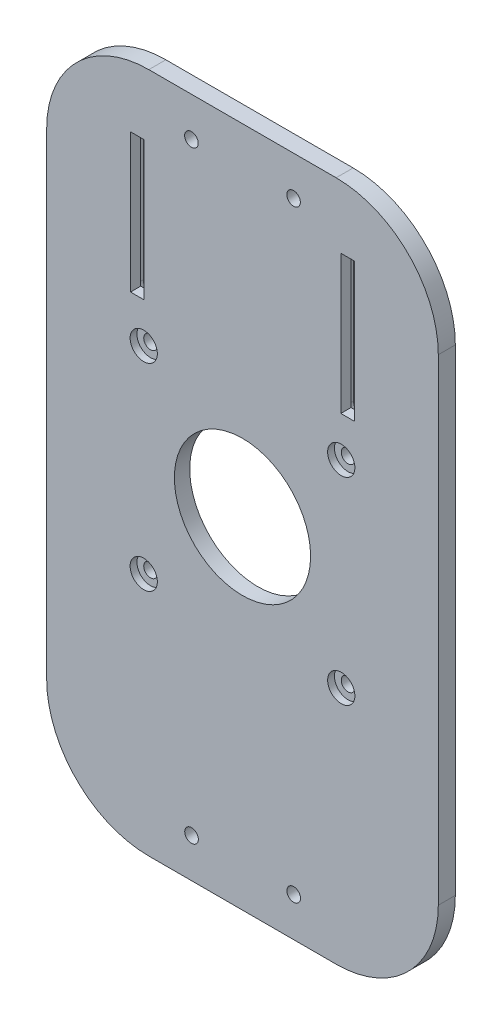
SolidWorks part; units mm, degrees
ref_plane "Front Plane" through (0, 0, 0) normal (1, 0, 0) x (0, 1, 0)
ref_plane "Top Plane" through (0, 0, 0) normal (0, 0, 1) x (0, 1, 0)
ref_plane "Right Plane" through (0, 0, 0) normal (0, 1, 0) x (-1, 0, 0)
sketch "Sketch1" plane through (0, 0, 0) normal (0, 0, 1) x (0, 1, 0)
  line L1 (-100, -57.5) -> (100, -57.5)
  line L2 (-100, -57.5) -> (-100, 57.5)
  line L3 (-100, 57.5) -> (100, 57.5)
  line L4 (100, -57.5) -> (100, 57.5)
  line L5 (-100, -57.5) -> (100, 57.5) construction
  line L6 (-100, 57.5) -> (100, -57.5) construction
  circle A0 centre (0, 0) radius 20
  point P0 (0, 0)
  dimension "D3" = 40
  dimension "D1" = 115
  dimension "D2" = 200
extrude "Boss-Extrude1" add sketch "Sketch1" along normal blind 5
sketch "Sketch4" plane through (0, 0, 5) normal (0, 0, 1) x (1, 0, 0)
  line L0 (0, 100) -> (0, -100) construction
  line L1 (57.5, 100) -> (-57.5, 100) construction
  line L2 (-57.5, -100) -> (57.5, -100) construction
  line L3 (-57.5, 0) -> (57.5, 0) construction
  line L4 (-57.5, 100) -> (-57.5, -100) construction
  line L5 (57.5, -100) -> (57.5, 100) construction
  circle A0 centre (29, 29) radius 2 construction
  circle A1 centre (-29, 29) radius 2 construction
  circle A2 centre (-29, -29) radius 2 construction
  circle A3 centre (29, -29) radius 2 construction
  circle A4 centre (29, 29) radius 2
  circle A5 centre (-29, 29) radius 2
  circle A6 centre (-29, -29) radius 2
  circle A7 centre (29, -29) radius 2
extrude "Cut-Extrude1" cut sketch "Sketch4" against normal up to next
sketch "Sketch5" plane through (0, 0, 5) normal (0, 0, 1) x (1, 0, 0)
  circle A0 centre (29, 29) radius 2 construction
  circle A1 centre (29, -29) radius 2 construction
  circle A3 centre (-29, 29) radius 2 construction
  circle A6 centre (-29, -29) radius 2 construction
  circle A40 centre (-29, -29) radius 2 construction
  circle A41 centre (-29, 29) radius 2 construction
  circle A42 centre (29, -29) radius 2 construction
  circle A43 centre (29, 29) radius 2 construction
  circle A44 centre (-29, -29) radius 4
  circle A45 centre (-29, 29) radius 4
  circle A46 centre (29, -29) radius 4
  circle A47 centre (29, 29) radius 4
  dimension "D1" = 2
extrude "Cut-Extrude2" cut sketch "Sketch5" against normal blind 2
fillet "Fillet1" radius 30 4 edges at (57.5, 100, 2.5) (-57.5, 100, 2.5) (-57.5, -100, 2.5) (57.5, -100, 2.5)
sketch "Sketch8" plane through (0, 0, 5) normal (0, 0, 1) x (1, 0, 0)
  circle A0 centre (15, 88.5) radius 2
  circle A1 centre (-15, 88.5) radius 2
  circle A2 centre (-14.9609, -88.5) radius 2
  circle A3 centre (15.0391, -88.5) radius 2
extrude "Cut-Extrude4" cut sketch "Sketch8" against normal through all
sketch "Sketch11" plane through (0, 0, 0) normal (0, 0, -1) x (1, 0, 0)
  line L1 (-35.75, -35.75) -> (35.75, -35.75)
  line L2 (-35.75, -35.75) -> (-35.75, 35.75)
  line L3 (-35.75, 35.75) -> (35.75, 35.75)
  line L4 (35.75, -35.75) -> (35.75, 35.75)
  line L5 (-35.75, -35.75) -> (35.75, 35.75) construction
  line L6 (-35.75, 35.75) -> (35.75, -35.75) construction
  point P0 (0, 0)
  dimension "D1" = 71.5
extrude "Cut-Extrude7" cut sketch "Sketch11" against normal blind 0.5
sketch "Sketch9" plane through (0, 0, 5) normal (0, 0, 1) x (1, 0, 0)
  line L0 (0, 0) -> (0, 100) construction
  line L1 (27.5, 100) -> (-27.5, 100) construction
  line L2 (-15.5, 76.5) -> (-15.5, 26.6053) construction
  line L3 (-17.5, 76.5) -> (-17.5, 27) construction
  line L4 (-13.5, 76.5) -> (-13.5, 27) construction
  line L5 (15.5, 76.5) -> (15.5, 26.6053) construction
  line L6 (17.5, 76.5) -> (17.5, 27) construction
  line L7 (13.5, 76.5) -> (13.5, 27) construction
  line L8 (21, 76.5) -> (21, 35.0212) construction
  line L9 (-21, 76.5) -> (-21, 35.0212) construction
  line L10 (28.875, 81.5) -> (28.875, 40.75)
  line L11 (28.875, 40.75) -> (32.875, 40.75)
  line L12 (32.875, 40.75) -> (32.875, 81.5)
  line L13 (32.875, 81.5) -> (28.875, 81.5)
  line L14 (-32.875, 40.75) -> (-32.875, 81.5)
  line L15 (-28.875, 40.75) -> (-32.875, 40.75)
  line L16 (-28.875, 81.5) -> (-28.875, 40.75)
  line L17 (-32.875, 81.5) -> (-28.875, 81.5)
  line L18 (-35.75, 35.75) -> (35.75, 35.75) construction
  arc A0 (-17.5, 76.5) -> (-13.5, 76.5) centre (-15.5, 76.5) cw construction
  arc A1 (-17.5, 27) -> (-13.5, 27) centre (-15.5, 27) ccw construction
  arc A2 (17.5, 76.5) -> (13.5, 76.5) centre (15.5, 76.5) ccw construction
  arc A3 (17.5, 27) -> (13.5, 27) centre (15.5, 27) cw construction
  circle A6 centre (-15, 88.5) radius 2 construction
  circle A11 centre (0, 0) radius 20 construction
  circle A14 centre (15, 88.5) radius 2 construction
  point P41 (-30.875, 81.5)
  point P42 (30.875, 81.5)
  dimension "D3" = 10
  dimension "D4" = 2
  dimension "D5" = 5
  dimension "D8" = 5
  dimension "D9" = 5
  dimension "D1" = 31
  dimension "D2" = 4
  dimension "D6" = 42
  dimension "D7" = 4
  dimension "D10" = 61.75
extrude "Cut-Extrude5" cut sketch "Sketch9" against normal through all
sketch "Sketch12" plane through (0, 0, 0) normal (0, 0, -1) x (1, 0, 0)
  line L0 (0, 0) -> (0, -100) construction
  line L3 (27.5, -100) -> (-27.5, -100) construction
  line L6 (-30.875, -40.75) -> (-30.875, -81.5) construction
  line L7 (-32.875, -40.75) -> (-28.875, -40.75) construction
  line L8 (-28.875, -81.5) -> (-32.875, -81.5) construction
  line L9 (-30.875, -81.5) -> (-30.875, -40.75) construction
  line L10 (-34.125, -81.5) -> (-34.125, -40.75)
  line L11 (-27.625, -81.5) -> (-27.625, -40.75)
  line L12 (30.875, -81.5) -> (30.875, -40.75) construction
  line L13 (34.125, -81.5) -> (34.125, -40.75)
  line L14 (27.625, -81.5) -> (27.625, -40.75)
  arc A0 (-34.125, -81.5) -> (-27.625, -81.5) centre (-30.875, -81.5) ccw
  arc A1 (-27.625, -40.75) -> (-34.125, -40.75) centre (-30.875, -40.75) ccw
  arc A2 (34.125, -81.5) -> (27.625, -81.5) centre (30.875, -81.5) cw
  arc A3 (27.625, -40.75) -> (34.125, -40.75) centre (30.875, -40.75) cw
  point P10 (-30.875, -61.125)
  point P18 (30.875, -61.125)
  dimension "D1" = 6.5
extrude "Cut-Extrude8" cut sketch "Sketch12" against normal blind 2
